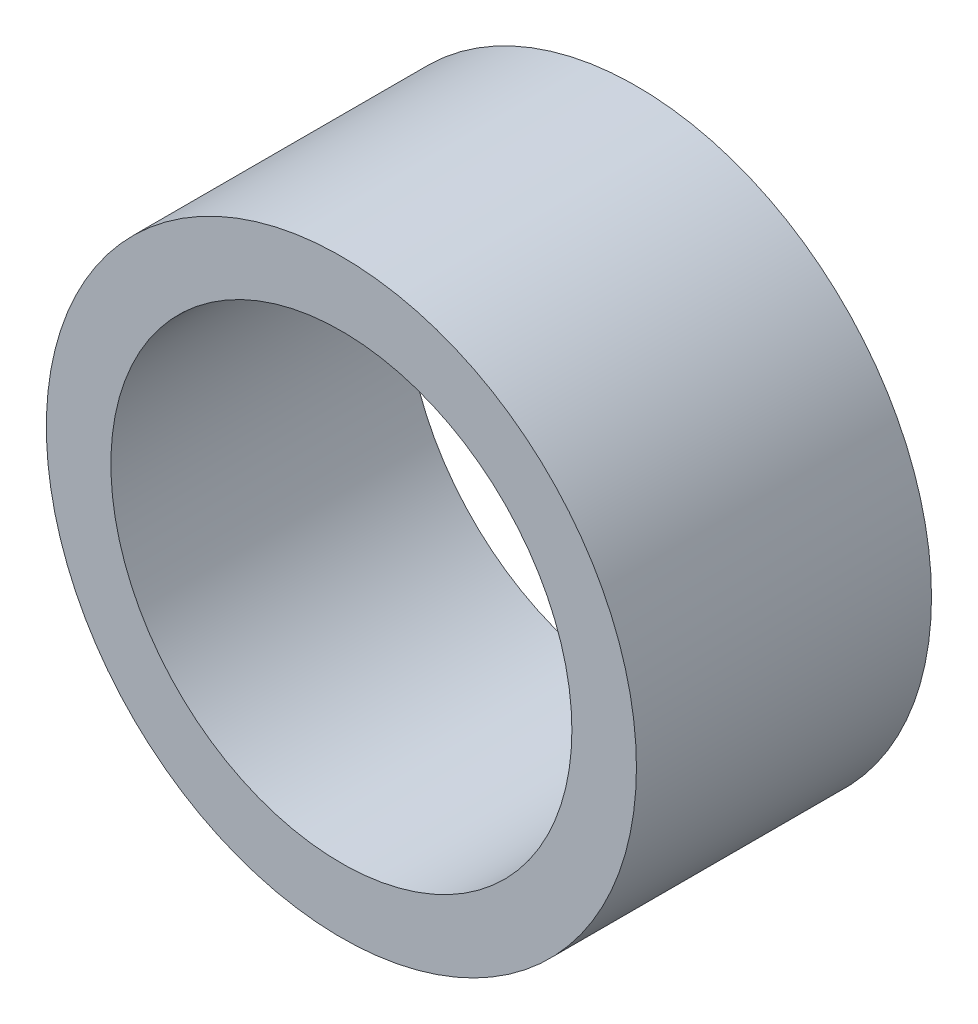
SolidWorks part; units mm, degrees
ref_plane "Alzado" through (0, 0, 0) normal (0, 0, 1) x (1, 0, 0)
ref_plane "Planta" through (0, 0, 0) normal (0, 1, 0) x (1, 0, 0)
ref_plane "Vista lateral" through (0, 0, 0) normal (1, 0, 0) x (0, 0, -1)
sketch "Croquis1" plane through (0, 0, 0) normal (0, 0, 1) x (1, 0, 0)
  circle A0 centre (0, 0) radius 16
  circle A1 centre (0, 0) radius 12.5
  dimension "D1" = 25
  dimension "D2" = 32
extrude "Saliente-Extruir1" add sketch "Croquis1" along normal blind 16
